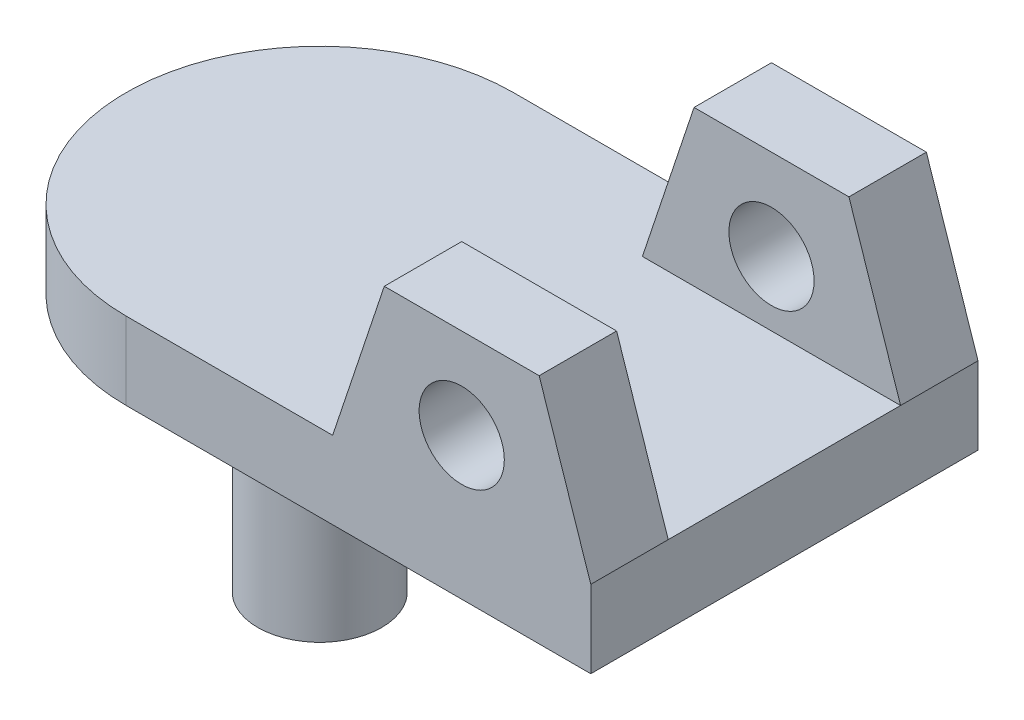
SolidWorks part; units mm, degrees
ref_plane "前视基准面" through (0, 0, 0) normal (0, 0, 1) x (1, 0, 0)
ref_plane "上视基准面" through (0, 0, 0) normal (0, 1, 0) x (1, 0, 0)
ref_plane "右视基准面" through (0, 0, 0) normal (1, 0, 0) x (0, 0, -1)
other "Configuration Table"
sketch "草图1" plane through (0, 0, 0) normal (0, 1, 0) x (1, 0, 0)
  line L1 (0, 7.5) -> (18, 7.5)
  line L2 (0, -7.5) -> (18, -7.5)
  line L3 (18, 7.5) -> (18, -7.5)
  arc A0 (0, 7.5) -> (0, -7.5) centre (0, 0) ccw
  point P3 (9.2025, 0)
  dimension "D1" = 7.5
  dimension "D2" = 18
extrude "凸台-拉伸1" add sketch "草图1" along normal blind 3
sketch "草图2" plane through (0, 0, 0) normal (0, -1, 0) x (1, 0, 0)
  circle A0 centre (0, 0) radius 2.4
  dimension "D1" = 4.8
extrude "凸台-拉伸2" add sketch "草图2" along normal blind 10
sketch "草图3" plane through (0, 0, 7.5) normal (0, 0, 1) x (1, 0, 0)
  line L0 (18, 3) -> (8, 3)
  line L1 (0, 3) -> (18, 3) construction
  line L2 (8, 3) -> (10, 9)
  line L3 (10, 9) -> (16, 9)
  line L4 (16, 9) -> (18, 3)
  dimension "D1" = 6
  dimension "D2" = 10
  dimension "D3" = 6
extrude "凸台-拉伸3" add sketch "草图3" against normal blind 3
mirror "镜向1" about plane through (0, 0, 0) normal (0, 0, 1) of "凸台-拉伸3"
sketch "草图4" plane through (0, 0, 7.5) normal (0, 0, 1) x (1, 0, 0)
  line L0 (13, 8) -> (13, 11.3621) construction
  line L2 (16, 9) -> (10, 9) construction
  circle A0 centre (13, 5.5) radius 1.65
  dimension "D1" = 3.3
  dimension "D2" = 3.5
extrude "切除-拉伸1" cut sketch "草图4" against normal through all
